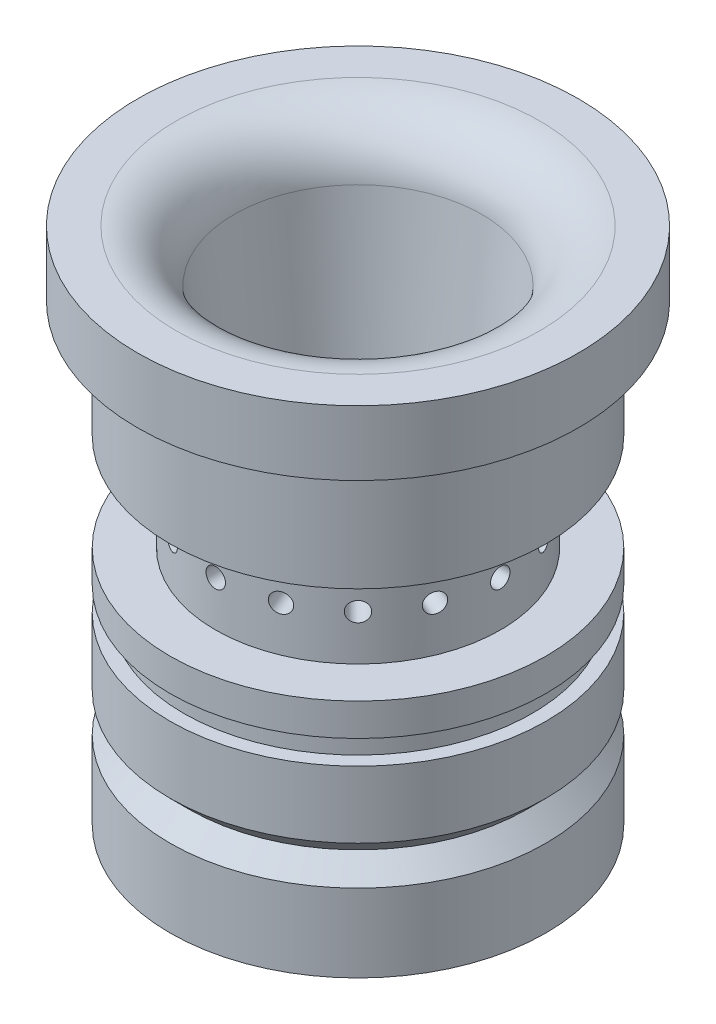
SolidWorks part; units mm, degrees
ref_plane "Alzado" through (0, 0, 0) normal (0, 0, 1) x (1, 0, 0)
ref_plane "Planta" through (0, 0, 0) normal (0, 1, 0) x (1, 0, 0)
ref_plane "Vista lateral" through (0, 0, 0) normal (1, 0, 0) x (0, 0, -1)
sketch "Sketch1" plane through (0, 0, 0) normal (0, 0, 1) x (1, 0, 0)
  line L0 (21.5, -44) -> (16.0195, 0)
  line L1 (21.5, -44) -> (29, -44)
  line L2 (29, -44) -> (29, -32)
  line L3 (29, -32) -> (26, -29)
  line L4 (26, -29) -> (29, -26)
  line L5 (29, -26) -> (29, -15.7)
  line L6 (29, -15.7) -> (26.9, -15.7)
  line L7 (26.9, -15.7) -> (26.9, -12)
  line L8 (26.9, -12) -> (29, -12)
  line L9 (29, -12) -> (29, -7)
  line L10 (29, -7) -> (22, -7)
  line L11 (22, -7) -> (22, 8)
  line L12 (22, 8) -> (29, 8)
  line L13 (29, 8) -> (29, 26)
  line L14 (29, 26) -> (34, 26)
  line L15 (34, 26) -> (34, 36)
  line L16 (34, 36) -> (28.055, 36)
  line L17 (19.1094, 27.9876) -> (16.0195, 0)
  line L18 (0, 70.21) -> (0, -70.21) construction
  arc A0 (28.055, 36) -> (19.1094, 27.9876) centre (28.055, 27) ccw
  dimension "D7" = 6.3
  dimension "D3" = 9
  dimension "D1" = 21.5
  dimension "D2" = 7.1
  dimension "D4" = 22
  dimension "D5" = 26.9
  dimension "D6" = 6
  dimension "D8" = 10
  dimension "D9" = 28
  dimension "D10" = 43
  dimension "D11" = 48
  dimension "D12" = 3.7
  dimension "D13" = 65
  dimension "D14" = 29
  dimension "D15" = 80
  dimension "D16" = 34
  dimension "D17" = 36
revolve "Revolve1" add sketch "Sketch1" angle 360 about L18
sketch "Sketch2" plane through (0, 0, 0) normal (1, 0, 0) x (0, 0, -1)
  circle A0 centre (0, 0) radius 1.5
  dimension "D1" = 3
extrude "Cut-Extrude3" cut sketch "Sketch2" against normal through all
pattern_circular "CirPattern1" count 16 over 360 about axis through (0, 70.21, 0) along (0, 1, 0) of "Cut-Extrude3"
